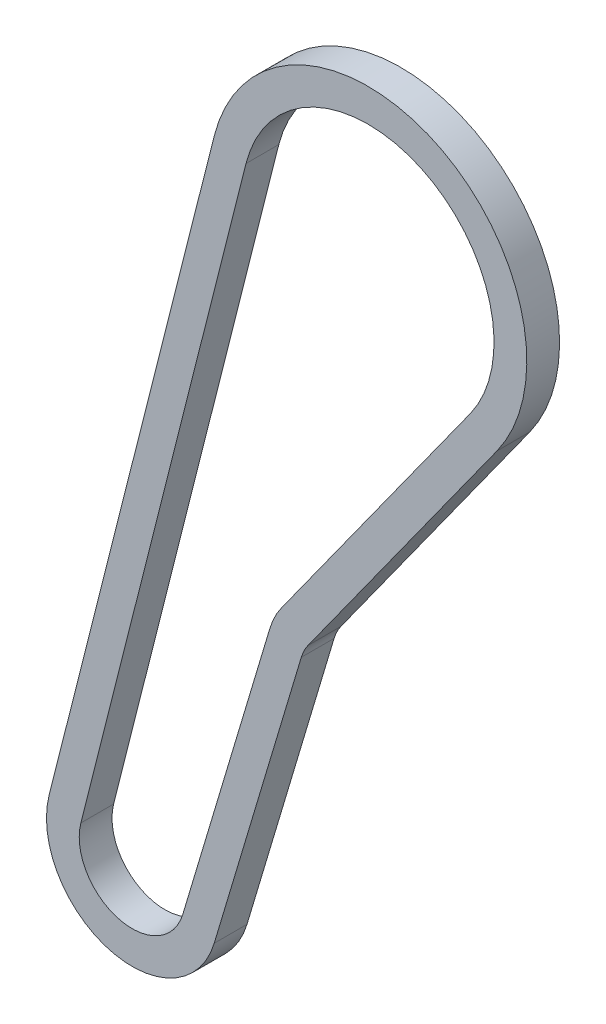
SolidWorks part; units mm, degrees
material "NEOPRENE"
ref_plane "Front Plane" through (0, 0, 0) normal (0, 0, 1) x (1, 0, 0)
ref_plane "Top Plane" through (0, 0, 0) normal (0, 1, 0) x (1, 0, 0)
ref_plane "Right Plane" through (0, 0, 0) normal (1, 0, 0) x (0, 0, -1)
sketch "Sketch2" plane through (0, 0, 0) normal (0, 0, 1) x (1, 0, 0)
  line L0 (0, 0) -> (1, 0) construction
  line L1 (0, 0) -> (0, 1) construction
  line L2 (-6.7418, 11.9518) -> (18.4577, 111.6808)
  line L4 (61.589, 91.6202) -> (32.7596, 51.5091)
  line L5 (31.7372, 49.4293) -> (18.452, 5.0051)
  arc A0 (18.452, 5.0051) -> (-6.7418, 11.9518) centre (5.93, 8.7499) cw
  arc A1 (18.4577, 111.6808) -> (61.589, 91.6202) centre (41.93, 105.7499) cw
  arc A2 (32.7596, 51.5091) -> (31.7372, 49.4293) centre (38.4437, 47.4237) ccw
extrude "Extrude-Thin1" add sketch "Sketch2" along normal blind 5 thin
